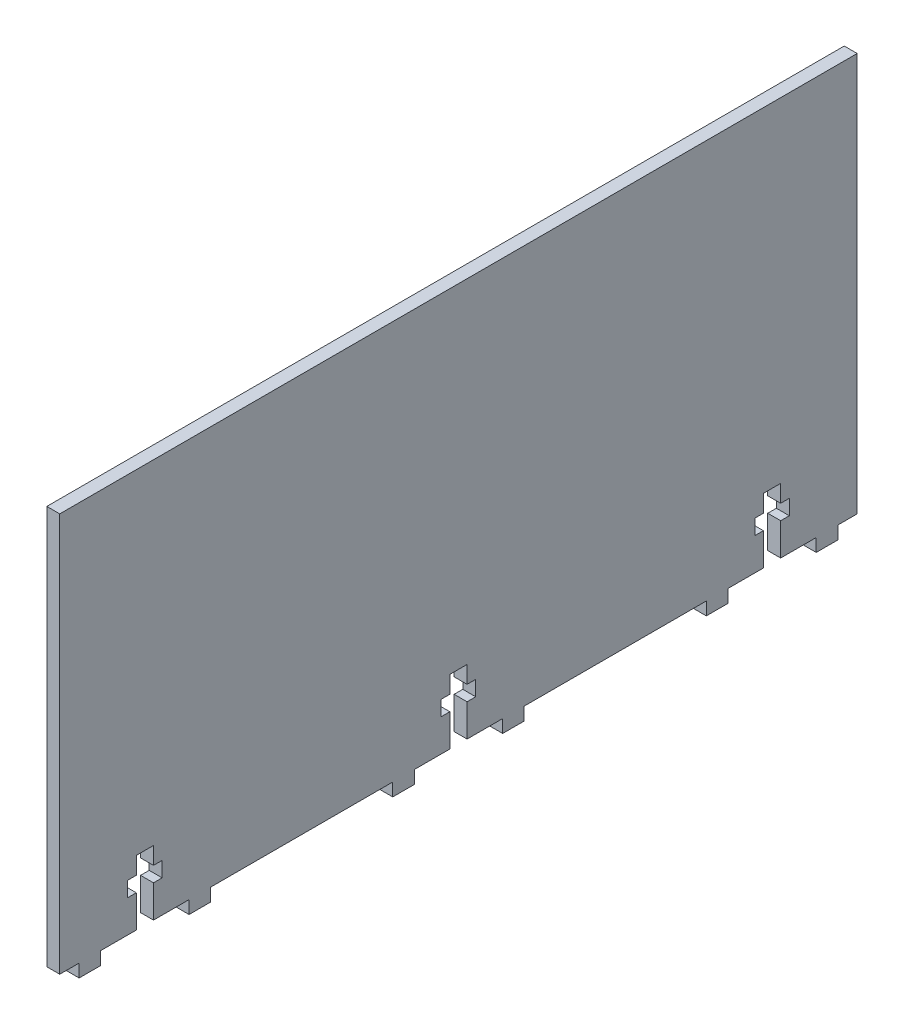
SolidWorks part; units mm, degrees
ref_plane "Front Plane" through (0, 0, 0) normal (0, 0, 1) x (1, 0, 0)
ref_plane "Top Plane" through (0, 0, 0) normal (0, 1, 0) x (1, 0, 0)
ref_plane "Right Plane" through (0, 0, 0) normal (1, 0, 0) x (0, 0, -1)
sketch "Sketch1" plane through (0, 0, 0) normal (1, 0, 0) x (0, 0, -1)
  line L0 (-185, -92.5) -> (185, 92.5) construction
  line L1 (-185, 92.5) -> (185, 92.5)
  line L2 (-185, 92.5) -> (-185, -92.5)
  line L3 (-185, -92.5) -> (-176, -92.5)
  line L4 (185, 92.5) -> (185, -92.5)
  line L5 (0, 92.5) -> (0, -92.5) construction
  line L6 (149.5, -92.5) -> (149.5, -77.5)
  line L7 (149.5, -77.5) -> (153.5, -77.5)
  line L8 (153.5, -77.5) -> (153.5, -70.5)
  line L9 (153.5, -70.5) -> (149.5, -70.5)
  line L10 (149.5, -70.5) -> (149.5, -62.5)
  line L11 (149.5, -62.5) -> (141.5, -62.5)
  line L12 (141.5, -62.5) -> (141.5, -70.5)
  line L13 (141.5, -70.5) -> (137.5, -70.5)
  line L14 (137.5, -70.5) -> (137.5, -77.5)
  line L15 (137.5, -77.5) -> (141.5, -77.5)
  line L16 (141.5, -77.5) -> (141.5, -92.5)
  line L17 (166, -92.5) -> (166, -98.5)
  line L18 (166, -98.5) -> (176, -98.5)
  line L19 (176, -98.5) -> (176, -92.5)
  line L20 (115, -92.5) -> (115, -98.5)
  line L21 (115, -98.5) -> (125, -98.5)
  line L22 (125, -98.5) -> (125, -92.5)
  line L23 (30.5, -92.5) -> (30.5, -98.5)
  line L24 (30.5, -98.5) -> (20.5, -98.5)
  line L25 (20.5, -98.5) -> (20.5, -92.5)
  line L26 (-20.5, -92.5) -> (-20.5, -98.5)
  line L27 (-20.5, -98.5) -> (-30.5, -98.5)
  line L28 (-30.5, -98.5) -> (-30.5, -92.5)
  line L29 (-115, -92.5) -> (-115, -98.5)
  line L30 (-115, -98.5) -> (-125, -98.5)
  line L31 (-125, -98.5) -> (-125, -92.5)
  line L32 (-176, -92.5) -> (-176, -98.5)
  line L33 (-176, -98.5) -> (-166, -98.5)
  line L34 (-166, -98.5) -> (-166, -92.5)
  line L35 (166, -95.5) -> (125, -95.5) construction
  line L36 (115, -95.5) -> (30.5, -95.5) construction
  line L37 (20.5, -95.5) -> (-20.5, -95.5) construction
  line L38 (-30.5, -95.5) -> (-115, -95.5) construction
  line L39 (-125, -95.5) -> (-166, -95.5) construction
  line L40 (-166, -92.5) -> (-125, -92.5)
  line L41 (-115, -92.5) -> (-30.5, -92.5)
  line L42 (-20.5, -92.5) -> (20.5, -92.5)
  line L43 (30.5, -92.5) -> (115, -92.5)
  line L44 (125, -92.5) -> (166, -92.5)
  line L45 (145.5, -62.5) -> (145.5, -92.5) construction
  line L46 (176, -92.5) -> (185, -92.5)
  line L47 (72.75, -92.5) -> (72.75, 92.5) construction
  line L48 (-4, -92.5) -> (-4, -77.5)
  line L49 (-4, -77.5) -> (-8, -77.5)
  line L50 (-8, -77.5) -> (-8, -70.5)
  line L51 (-8, -70.5) -> (-4, -70.5)
  line L52 (-4, -70.5) -> (-4, -62.5)
  line L53 (-4, -62.5) -> (4, -62.5)
  line L54 (4, -62.5) -> (4, -70.5)
  line L55 (4, -70.5) -> (8, -70.5)
  line L56 (8, -70.5) -> (8, -77.5)
  line L57 (8, -77.5) -> (4, -77.5)
  line L58 (4, -77.5) -> (4, -92.5)
  line L59 (-149.5, -92.5) -> (-149.5, -77.5)
  line L60 (-149.5, -77.5) -> (-153.5, -77.5)
  line L61 (-153.5, -77.5) -> (-153.5, -70.5)
  line L62 (-153.5, -70.5) -> (-149.5, -70.5)
  line L63 (-149.5, -70.5) -> (-149.5, -62.5)
  line L64 (-149.5, -62.5) -> (-141.5, -62.5)
  line L65 (-141.5, -62.5) -> (-141.5, -70.5)
  line L66 (-141.5, -70.5) -> (-137.5, -70.5)
  line L67 (-137.5, -70.5) -> (-137.5, -77.5)
  line L68 (-141.5, -77.5) -> (-141.5, -92.5)
  line L69 (-137.5, -77.5) -> (-141.5, -77.5)
  dimension "D1" = 370
  dimension "D2" = 185
  dimension "D3" = 8
  dimension "D4" = 8
  dimension "D5" = 7
  dimension "D6" = 15
  dimension "D7" = 4
  dimension "D8" = 10
  dimension "D9" = 6
  dimension "D10" = 9
  dimension "D11" = 84.5
  dimension "D12" = 41
extrude "Boss-Extrude1" add sketch "Sketch1" along normal mid plane 6 contours L67 L69 L68 L40 L31 L30 L29 L41 L28 L27 L26 L42 L48 L49 L50 L51 L52 L53 L54 L55 L56 L57 L58 L25 L24 L23 L43 L20 L21 L22 L44 L16 L15 L14 L13 L12 L11 L10 L9 L8 L7 L6 L17 L18 L19 L46 L4 L1 L2
